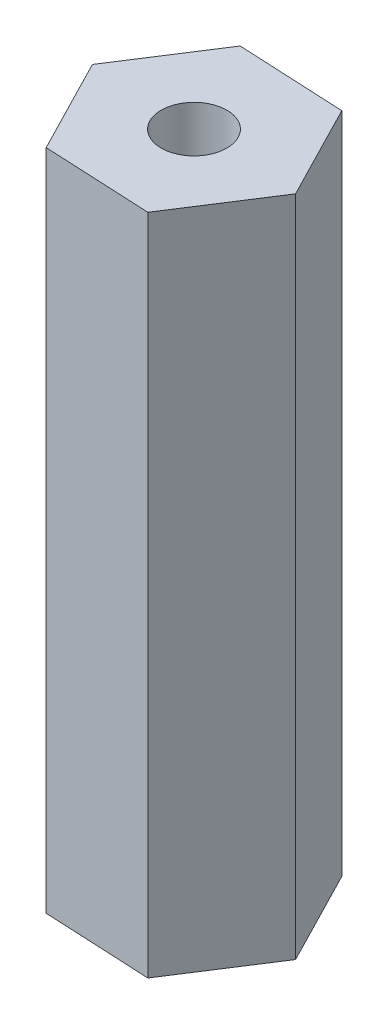
SolidWorks part; units mm, degrees
ref_plane "Front Plane" through (0, 0, 0) normal (0, 0, 1) x (1, 0, 0)
ref_plane "Top Plane" through (0, 0, 0) normal (0, 1, 0) x (1, 0, 0)
ref_plane "Right Plane" through (0, 0, 0) normal (1, 0, 0) x (0, 0, -1)
sketch "Sketch1" plane through (0, 0, 0) normal (0, 1, 0) x (1, 0, 0)
  line L1 (-1.6363, 3.1837) -> (-3.5753, 0.1747)
  line L2 (-3.5753, 0.1747) -> (-1.939, -3.0089)
  line L3 (-1.939, -3.0089) -> (1.6363, -3.1837)
  line L4 (1.6363, -3.1837) -> (3.5753, -0.1747)
  line L5 (3.5753, -0.1747) -> (1.939, 3.0089)
  line L6 (1.939, 3.0089) -> (-1.6363, 3.1837)
  circle A0 centre (0, 0) radius 3.1 construction
  dimension "D1" = 6.2
extrude "Boss-Extrude1" add sketch "Sketch1" along normal blind 22.2 contours L1 L2 L3 L4 L5 L6
sketch "Sketch2" plane through (0, 0, 0) normal (0, -1, 0) x (1, 0, 0)
  circle A0 centre (0, 0) radius 1.1
extrude "Cut-Extrude1" cut sketch "Sketch2" against normal through all
equation "\"MDF\"= 4.8mm"
equation "\"Foamcore\"= 4.6mm"
equation "\"PCB\" = 1.6mm"
equation "\"GMaterial\"= \"MDF\""
equation "\"BaseWidth\" = 10in"
equation "\"SkidLength\" = 1in"
equation "\"SkidClearance\" = 0.4in"
equation "\"MotorMountLength\" = 2in"
equation "\"MotorMountWidth\" = \"GMaterial\""
equation "\"MotorMountHeight\" = 2.25in"
equation "\"UnoStackWidth\" = 77.4mm"
equation "\"UnoStackLength\" = 79.8mm"
equation "\"UnoStackHeight\" = 34.2mm"
equation "\"TallHexRiserHeight\" = 22.2mm"
equation "\"D1@Boss-Extrude1\"=\"TallHexRiserHeight\""
